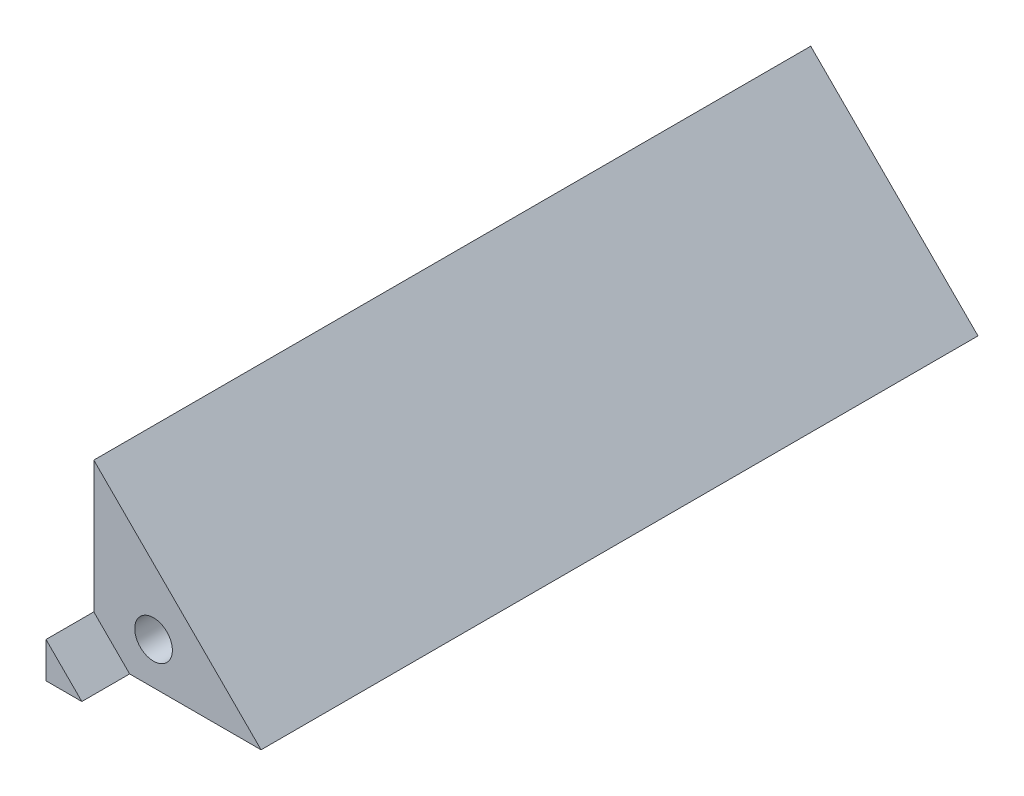
SolidWorks part; units mm, degrees
ref_plane "Plano frontal" through (0, 0, 0) normal (0, 0, 1) x (1, 0, 0)
ref_plane "Plano superior" through (0, 0, 0) normal (0, 1, 0) x (1, 0, 0)
ref_plane "Plano direito" through (0, 0, 0) normal (1, 0, 0) x (0, 0, -1)
sketch "Esboço1" plane through (0, 0, 0) normal (0, 0, 1) x (1, 0, 0)
  line L0 (0, 0) -> (14, 0)
  line L1 (14, 0) -> (0, 14)
  line L2 (0, 14) -> (0, 0)
  dimension "D1" = 14
  dimension "D2" = 45
extrude "Ressalto-extrusão1" add sketch "Esboço1" along normal blind 60
sketch "Esboço2" plane through (0, 0, 60) normal (0, 0, 1) x (1, 0, 0)
  line L0 (0, 0) -> (0, 3)
  line L1 (0, 14) -> (0, 0) construction
  line L2 (0, 3) -> (3, 0)
  line L3 (0, 0) -> (14, 0) construction
  line L4 (3, 0) -> (0, 0)
  dimension "D1" = 3
  dimension "D2" = 3
extrude "Ressalto-extrusão2" add sketch "Esboço2" along normal blind 4
sketch "Esboço3" plane through (0, 0, 0) normal (0, 0, -1) x (-1, 0, 0)
  line L0 (0, 0) -> (0, 3)
  line L1 (0, 14) -> (0, 0) construction
  line L2 (0, 3) -> (-3, 0)
  line L3 (0, 0) -> (-14, 0) construction
  line L4 (-3, 0) -> (0, 0)
  dimension "D1" = 3
  dimension "D2" = 3
extrude "Ressalto-extrusão3" add sketch "Esboço3" along normal blind 4
hole_wizard "Furo roscado para conduíte de M3x0.51" positions "Esboço4" profile "Esboço6" tap size "M3x0.5" standard "Helicoil® Metric"
sketch "Esboço4" plane through (0, 0, 60) normal (0, 0, 1) x (1, 0, 0)
  line L0 (0, 14) -> (0, 3) construction
  line L1 (3, 0) -> (14, 0) construction
  point P0 (5, 3.5)
  dimension "D1" = 5
  dimension "D2" = 3.5
sketch "Esboço6" plane through (5, 3.5, 60) normal (1, 0, 0) x (0, -1, 0)
  line L0 (0, 0) -> (0, 10.9464)
  line L1 (0, 10.9464) -> (1.575, 10)
  line L2 (1.575, 10) -> (1.575, 0)
  line L5 (1.575, 0) -> (0, 0)
  line L10 (0, 10.9464) -> (-1.575, 10) construction
  line L11 (0, -6.35) -> (0, 107.95) construction
  dimension "Tap Drill Dia." = 3.15
  dimension "Tap Drill Depth" = 10
  dimension "Drill Angle" = 118
cosmetic thread "Rosca de furo1"
hole_wizard "Furo roscado para conduíte de M3x0.52" positions "Esboço7" profile "Esboço8" tap size "M3x0.5" standard "Helicoil® Metric"
sketch "Esboço7" plane through (0, 0, 0) normal (0, 0, -1) x (-1, 0, 0)
  line L0 (0, 14) -> (0, 3) construction
  line L1 (-3, 0) -> (-14, 0) construction
  point P0 (-5, 3.5)
  dimension "D1" = 5
  dimension "D2" = 3.5
sketch "Esboço8" plane through (5, 3.5, 0) normal (1, 0, 0) x (0, 1, 0)
  line L0 (0, 0) -> (0, 8.4464)
  line L1 (0, 8.4464) -> (1.575, 7.5)
  line L2 (1.575, 7.5) -> (1.575, 0)
  line L5 (1.575, 0) -> (0, 0)
  line L10 (0, 8.4464) -> (-1.575, 7.5) construction
  line L11 (0, -6.35) -> (0, 107.95) construction
  dimension "Tap Drill Dia." = 3.15
  dimension "Tap Drill Depth" = 7.5
  dimension "Drill Angle" = 118
cosmetic thread "Rosca de furo2"
